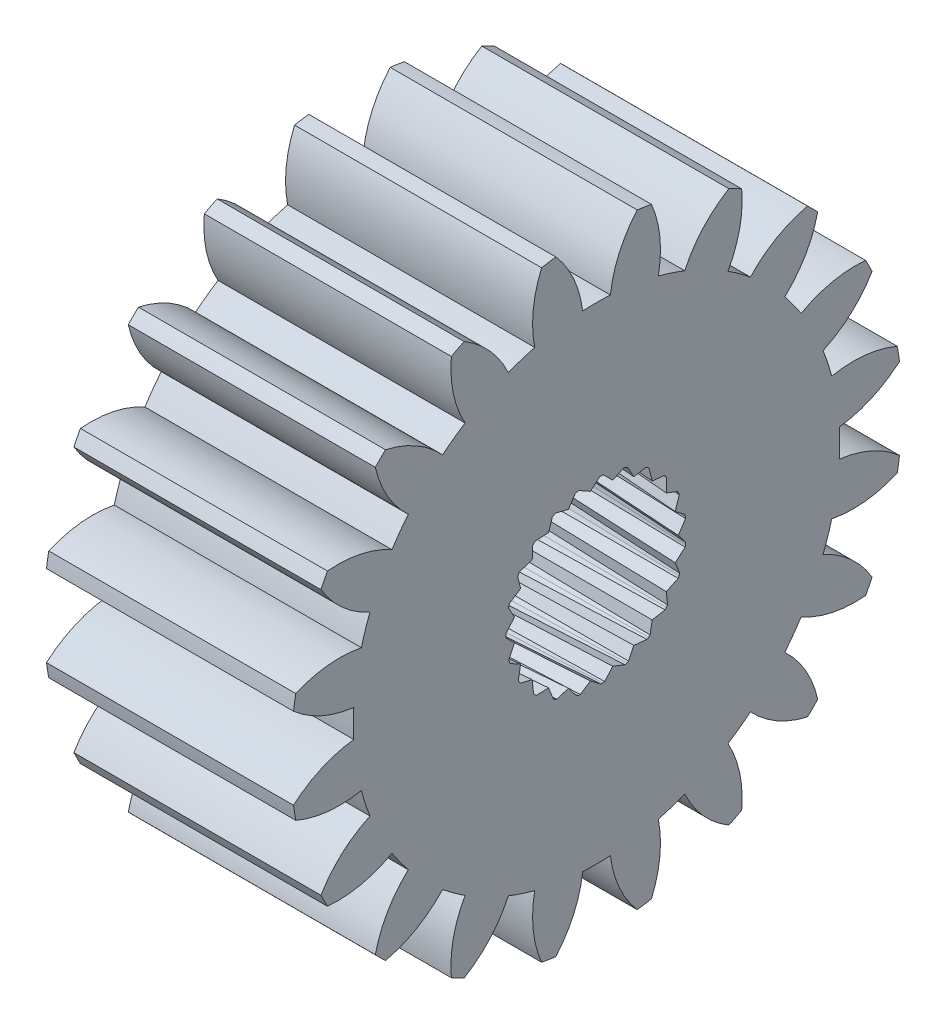
SolidWorks part; units mm, degrees
ref_plane "Plane1" through (0, 0, 0) normal (0, 0, 1) x (1, 0, 0)
ref_plane "Plane2" through (0, 0, 0) normal (0, 1, 0) x (1, 0, 0)
ref_plane "Plane3" through (0, 0, 0) normal (1, 0, 0) x (0, 0, -1)
sketch "HoldingSke" plane through (0, 0, 0) normal (0, 1, 0) x (1, 0, 0)
  line L0 (0, 0) -> (1.0441, -0.38)
  line L1 (-15, 0) -> (100, 0) construction
  line L2 (0, 0) -> (-2.1039, 2.3779)
  line L3 (0, 0) -> (-11.863, 4.5341)
  line L4 (0, 0) -> (8.1152, 2.9537)
  line L5 (0, 0) -> (-46.8476, -17.4728)
  line L6 (0, 0) -> (-6.6317, -4.4744)
  line L7 (-2.1039, 2.3779) -> (8.6586, 51.2059)
  line L8 (-76.2, 54.61) -> (-76.1, 54.61)
  line L9 (-71.009, 38.7566) -> (-53.1078, 45.2721)
  line L10 (-76.2, 71.12) -> (104.1128, 71.12)
  line L11 (0, 0) -> (-8, 0)
  line L12 (-76.2, 101.6) -> (-76.166, 101.6)
  line L13 (24.9733, 27.94) -> (52.9518, 28.4284)
  line L14 (24.9733, 27.94) -> (24.9743, 27.94)
  line L15 (24.9733, 27.94) -> (100.4006, 29.5858)
  line L16 (-63.627, -0.9) -> (-12.827, -0.9)
  circle A0 centre (0, 0) radius 0.4
  circle A1 centre (0, 0) radius 7.874
  circle A2 centre (0, 0) radius 37.5
  circle A3 centre (0, 0) radius 0.4
  dimension "MHD" = 15.748
  dimension "Hub_dia" = 75
  dimension "Bore" = 0.8
  dimension "MBD" = 0.8
  dimension "Num_teeth" = 20
  dimension "Pitch" = 1.1111
  dimension "Overall_len" = 50
  dimension "Show_teeth" = 20
  dimension "Thickness" = 8
  dimension "OAL" = 50.0001
  dimension "T_dim" = 0.1
  dimension "Ap" = 20
  dimension "H" = 19.05
  dimension "Pitch_radius" = 180.3128
  dimension "Width" = 8
  dimension "Backlash" = 0.034
  dimension "Addendum_fac" = 1
  dimension "Dedendum_fac" = 1.25
  dimension "Clearance_fac" = 0.25
  dimension "Dedendum_add" = 0.001
  dimension "Module" = 0.9
sketch "BasProSke" plane through (0, 0, 0) normal (0, 1, 0) x (1, 0, 0)
  line L0 (-10, 0) -> (60, 0) construction
  line L1 (0, 0) -> (0, 9.9)
  line L2 (0, 0) -> (8, 0)
  line L3 (8, 0) -> (8, 9.9)
  line L4 (8, 9.9) -> (0, 9.9)
  dimension "Thickness" = 8
  dimension "Diameter" = 19.8
revolve "Base-Revolve" add sketch "BasProSke" angle 360 about L0
sketch "TooCutSke" plane through (0, 0, 0) normal (1, 0, 0) x (0, 0, -1)
  line L1 (0, 0) -> (0, 107) construction
  line L2 (0, 0) -> (-0.7656, 8.9674) construction
  line L3 (0, 0) -> (-2.8085, 17.7324) construction
  line L4 (-0.7656, 8.9674) -> (-1.4043, 8.8662) construction
  arc A0 (0.4496, 7.8612) -> (-0.4496, 7.8612) centre (0, 0) ccw
  arc A1 (1.3383, 9.8348) -> (-1.3383, 9.8348) centre (0, 0) ccw
  circle A2 centre (0, 0) radius 9 construction
  circle A3 centre (0, 0) radius 8.4572 construction
  arc A4 (-0.4496, 7.8612) -> (-1.3383, 9.8348) centre (-4.0247, 7.4382) ccw
  arc A5 (1.3383, 9.8348) -> (0.4496, 7.8612) centre (4.0247, 7.4382) ccw
  dimension "Root_dia" = 15.748
  dimension "Overcut_dia" = 19.8508
  dimension "Pitch_dia" = 18
  dimension "Base_dia" = 16.9145
  dimension "Flank_rad" = 3.6
  dimension "Half_ang" = 9
  dimension "Half_CT" = 0.6466
extrude "ToothCut" cut sketch "TooCutSke" along normal through all
fillet "Breaks" [suppressed] radius 0.018
fillet "RootFillets" [suppressed] radius 0.226
pattern_circular "TeethCuts" count 20 every 18 about axis through (-10, 0, 0) along (1, 0, 0) of "ToothCut", "RootFillets", "Breaks"
sketch "HubNeaOneSke" plane through (0, 0, 0) normal (-1, 0, 0) x (0, 0, 1)
  circle A0 centre (0, 0) radius 7.874
  dimension "Diameter" = 15.748
extrude "HubNearOne" [suppressed] add sketch "HubNeaOneSke" along normal blind 42.0001
sketch "HubNeaBotSke" plane through (0, 0, 0) normal (-1, 0, 0) x (0, 0, 1)
  circle A0 centre (0, 0) radius 7.874
  dimension "Diameter" = 15.748
extrude "HubNearBoth" [suppressed] add sketch "HubNeaBotSke" along normal blind 21
ref_plane "FarPln" through (8, 0, 0) normal (1, 0, 0) x (0, 0, -1)
sketch "HubFarSke" plane through (8, 0, 0) normal (1, 0, 0) x (0, 0, -1)
  circle A0 centre (0, 0) radius 7.874
  dimension "Diameter" = 15.748
extrude "HubFar" [suppressed] add sketch "HubFarSke" along normal blind 21
sketch "BorSke" plane through (0, 0, 0) normal (1, 0, 0) x (0, 0, -1)
  circle A0 centre (0, 0) radius 0.4
  dimension "Diameter" = 0.8
extrude "Bore" cut sketch "BorSke" along normal mid plane 100.0001
sketch "KeySke" plane through (0, 0, 0) normal (1, 0, 0) x (0, 0, -1)
  line L0 (-0.05, 0) -> (-0.05, 0.5)
  line L1 (-0.05, 0.5) -> (0.05, 0.5)
  line L2 (0.05, 0.5) -> (0.05, 0)
  line L3 (0, 0) -> (0, 34) construction
  line L4 (-0.05, 0) -> (0.05, 0)
  dimension "Offset" = 0.5
  dimension "Width" = 0.1
extrude "Keyway" [suppressed] cut sketch "KeySke" along normal mid plane 100.0001
pattern_circular "Keyway2" [suppressed] count 2 every 90 about axis through (-10, 0, 0) along (1, 0, 0)
sketch "Sketch1" plane through (8, 0, 0) normal (1, 0, 0) x (0, 0, -1)
  line L185 (-2.934, 0.0633) -> (-2.6551, 0.3832)
  line L186 (-2.9384, 0) -> (-2.934, 0.0633)
  line L187 (-2.9384, 0) -> (-2.934, -0.0633)
  line L188 (-2.934, -0.0633) -> (-2.6551, -0.3422)
  line L189 (-2.8143, 0.8489) -> (-2.4594, 1.0817)
  line L190 (-2.8355, 0.7892) -> (-2.8143, 0.8489)
  line L191 (-2.8355, 0.7892) -> (-2.8484, 0.7271)
  line L192 (-2.8484, 0.7271) -> (-2.6551, 0.3832)
  line L193 (-2.487, 1.5731) -> (-2.0825, 1.7015)
  line L194 (-2.5236, 1.5213) -> (-2.487, 1.5731)
  line L195 (-2.5236, 1.5213) -> (-2.5528, 1.465)
  line L196 (-2.5528, 1.465) -> (-2.4594, 1.0817)
  line L197 (-1.9765, 2.1822) -> (-1.5523, 2.1967)
  line L198 (-2.0257, 2.1422) -> (-1.9765, 2.1822)
  line L199 (-2.0257, 2.1422) -> (-2.069, 2.0958)
  line L200 (-2.069, 2.0958) -> (-2.0825, 1.7015)
  line L201 (-1.3206, 2.6309) -> (-0.9082, 2.5304)
  line L202 (-1.3788, 2.6057) -> (-1.3206, 2.6309)
  line L203 (-1.3788, 2.6057) -> (-1.4329, 2.5727)
  line L204 (-1.4329, 2.5727) -> (-1.5523, 2.1967)
  line L205 (-0.5679, 2.8861) -> (-0.1979, 2.678)
  line L206 (-0.6308, 2.8774) -> (-0.5679, 2.8861)
  line L207 (-0.6308, 2.8774) -> (-0.6918, 2.8603)
  line L208 (-0.6918, 2.8603) -> (-0.9082, 2.5304)
  line L209 (0.2257, 2.9287) -> (0.5258, 2.6285)
  line L210 (0.1628, 2.9373) -> (0.2257, 2.9287)
  line L211 (0.1628, 2.9373) -> (0.0994, 2.9373)
  line L212 (0.0994, 2.9373) -> (-0.1979, 2.678)
  line L213 (1.0013, 2.7556) -> (1.2093, 2.3856)
  line L214 (0.9431, 2.7808) -> (1.0013, 2.7556)
  line L215 (0.9431, 2.7808) -> (0.8821, 2.7979)
  line L216 (0.8821, 2.7979) -> (0.5258, 2.6285)
  line L217 (1.7015, 2.3796) -> (1.802, 1.9672)
  line L218 (1.6523, 2.4197) -> (1.7015, 2.3796)
  line L219 (1.6523, 2.4197) -> (1.5981, 2.4526)
  line L220 (1.5981, 2.4526) -> (1.2093, 2.3856)
  line L221 (2.2743, 1.8287) -> (2.2598, 1.4045)
  line L222 (2.2377, 1.8806) -> (2.2743, 1.8287)
  line L223 (2.2377, 1.8806) -> (2.1944, 1.9269)
  line L224 (2.1944, 1.9269) -> (1.802, 1.9672)
  line L225 (2.6772, 1.1437) -> (2.5488, 0.7392)
  line L226 (2.656, 1.2035) -> (2.6772, 1.1437)
  line L227 (2.656, 1.2035) -> (2.6268, 1.2598)
  line L228 (2.6268, 1.2598) -> (2.2598, 1.4045)
  line L229 (2.8804, 0.3754) -> (2.6476, 0.0205)
  line L230 (2.8761, 0.4387) -> (2.8804, 0.3754)
  line L231 (2.8761, 0.4387) -> (2.8632, 0.5008)
  line L232 (2.8632, 0.5008) -> (2.5488, 0.7392)
  line L233 (2.8687, -0.4192) -> (2.5488, -0.6982)
  line L234 (2.8816, -0.3571) -> (2.8687, -0.4192)
  line L235 (2.8816, -0.3571) -> (2.886, -0.2939)
  line L236 (2.886, -0.2939) -> (2.6476, 0.0205)
  line L237 (2.6431, -1.1813) -> (2.2598, -1.3636)
  line L238 (2.6723, -1.1249) -> (2.6431, -1.1813)
  line L239 (2.6723, -1.1249) -> (2.6935, -1.0652)
  line L240 (2.6935, -1.0652) -> (2.5488, -0.6982)
  line L241 (2.2203, -1.8542) -> (1.802, -1.9263)
  line L242 (2.2636, -1.8078) -> (2.2203, -1.8542)
  line L243 (2.2636, -1.8078) -> (2.3001, -1.756)
  line L244 (2.3001, -1.756) -> (2.2598, -1.3636)
  line L245 (1.6316, -2.388) -> (1.2093, -2.3446)
  line L246 (1.6858, -2.3551) -> (1.6316, -2.388)
  line L247 (1.6858, -2.3551) -> (1.735, -2.315)
  line L248 (1.735, -2.315) -> (1.802, -1.9263)
  line L249 (0.9207, -2.7433) -> (0.5258, -2.5876)
  line L250 (0.9817, -2.7262) -> (0.9207, -2.7433)
  line L251 (0.9817, -2.7262) -> (1.0399, -2.7009)
  line L252 (1.0399, -2.7009) -> (1.2093, -2.3446)
  line L253 (0.1403, -2.8935) -> (-0.1979, -2.6371)
  line L254 (0.2037, -2.8935) -> (0.1403, -2.8935)
  line L255 (0.2037, -2.8935) -> (0.2665, -2.8849)
  line L256 (0.2665, -2.8849) -> (0.5258, -2.5876)
  line L257 (-0.6517, -2.8277) -> (-0.9082, -2.4895)
  line L258 (-0.5906, -2.8448) -> (-0.6517, -2.8277)
  line L259 (-0.5906, -2.8448) -> (-0.5278, -2.8534)
  line L260 (-0.5278, -2.8534) -> (-0.1979, -2.6371)
  line L261 (-1.3966, -2.5506) -> (-1.5523, -2.1557)
  line L262 (-1.3424, -2.5835) -> (-1.3966, -2.5506)
  line L263 (-1.3424, -2.5835) -> (-1.2842, -2.6088)
  line L264 (-1.2842, -2.6088) -> (-0.9082, -2.4895)
  line L265 (-2.039, -2.0828) -> (-2.0825, -1.6606)
  line L266 (-1.9958, -2.1292) -> (-2.039, -2.0828)
  line L267 (-1.9958, -2.1292) -> (-1.9466, -2.1692)
  line L268 (-1.9466, -2.1692) -> (-1.5523, -2.1557)
  line L269 (-2.5315, -1.459) -> (-2.4594, -1.0408)
  line L270 (-2.5023, -1.5154) -> (-2.5315, -1.459)
  line L271 (-2.5023, -1.5154) -> (-2.4657, -1.5672)
  line L272 (-2.4657, -1.5672) -> (-2.0825, -1.6606)
  line L273 (-2.8374, -0.7256) -> (-2.6551, -0.3422)
  line L274 (-2.8245, -0.7876) -> (-2.8374, -0.7256)
  line L275 (-2.8245, -0.7876) -> (-2.8032, -0.8474)
  line L276 (-2.8032, -0.8474) -> (-2.4594, -1.0408)
  point P0 (0, 0)
  point P21 (0, 0)
  point P93 (-2.9362, -0.0316)
  point P123 (-0.0162, 0.0205)
  dimension "D1" = 2.6551
  dimension "D2" = 2.934
  dimension "D3" = 2.9362
  dimension "D4" = 0.0633
  dimension "D5" = 0.3627
  dimension "D6" = 23
  dimension "D8" = 0.3422
extrude "Cut-Extrude1" cut sketch "Sketch1" against normal blind 10 draft 3
sketch "Sketch2" plane through (8, 0, 0) normal (1, 0, 0) x (0, 0, -1)
  circle A0 centre (0, 0) radius 7.874
  arc A1 (-7.3375, 2.8568) -> (-7.6153, 2.0016) centre (0, 0) ccw construction
  dimension "D1" = 15.748
equation "' \"Module@HoldingSke\" = 6.35"
equation "' \"Num_teeth@HoldingSke\" = 12"
equation "' \"Ap@HoldingSke\" =  20"
equation "' \"Ap@HoldingSke\" = 20"
equation "' \"Width@HoldingSke\" = 0.5 * 25.4"
equation "' \"Hub_dia@HoldingSke\"= 1 * 25.4"
equation "' \"Hub_dia@HoldingSke\" = 1 * 25.4"
equation "' \"Overall_len@HoldingSke\" = 1.0 * 25.4"
equation "' \"Bore@HoldingSke\" = 0.75 * 25.4"
equation "' \"T_dim@HoldingSke\" = 0.1 * 25.4"
equation "' \"Width@KeySke\" = 0.25 * 25.4"
equation "' \"Show_teeth@HoldingSke\" = 13"
equation "' \"Backlash@HoldingSke\" = 0.009 * 25.4"
equation "' \"Addendum_fac@HoldingSke\" = 1.0"
equation "' \"Dedendum_fac@HoldingSke\" = 1.25"
equation "' \"Dedendum_add@HoldingSke\" = 0.00005 * 25.4"
equation "' \"Clearance_fac@HoldingSke\" = 0.25"
equation "\"Pitch@HoldingSke\" = 1 / \"Module@HoldingSke\""
equation "\"Overcut_dia@TooCutSke\" = (\"Num_teeth@HoldingSke\" + 2 * \"Addendum_fac@HoldingSke\") / \"Pitch@HoldingSke\" + 0.002 * 25.4"
equation "\"Pitch_dia@TooCutSke\" = \"Num_teeth@HoldingSke\" / \"Pitch@HoldingSke\""
equation "\"Base_dia@TooCutSke\" = \"Num_teeth@HoldingSke\" / \"Pitch@HoldingSke\" * cos((\"Ap@HoldingSke\"  * 3.14159265 / 180))"
equation "\"Root_dia@TooCutSke\" = (\"Num_teeth@HoldingSke\" + 2) / \"Pitch@HoldingSke\" - 2 * (\"Addendum_fac@HoldingSke\" + \"Dedendum_fac@HoldingSke\") / \"Pitch@HoldingSke\" - \"Dedendum_add@HoldingSke\" * 2"
equation "\"Half_ang@TooCutSke\" = 180 / \"Num_teeth@HoldingSke\""
equation "\"Half_CT@TooCutSke\" = \"Num_teeth@HoldingSke\" / \"Pitch@HoldingSke\" * sin((3.14159265 / 2 / \"Num_teeth@HoldingSke\")) / 2 - 7 * \"Backlash@HoldingSke\" / 4"
equation "\"Flank_rad@TooCutSke\" = \"Num_teeth@HoldingSke\" / \"Pitch@HoldingSke\" / 5"
equation "\"Radius@RootFillets\" = \"Clearance_fac@HoldingSke\" / \"Pitch@HoldingSke\" + \"Dedendum_add@HoldingSke\""
equation "\"Break_rad@Breaks\" = 0.02 / \"Pitch@HoldingSke\""
equation "\"Thickness@HoldingSke\" = \"Width@HoldingSke\""
equation "\"OAL@HoldingSke\" = \"Thickness@HoldingSke\""
equation "\"MHD@HoldingSke\" = (\"Num_teeth@HoldingSke\" + 2) / \"Pitch@HoldingSke\" - 2 * (\"Addendum_fac@HoldingSke\" + \"Dedendum_fac@HoldingSke\")  / \"Pitch@HoldingSke\" - \"Dedendum_add@HoldingSke\" * 2"
equation "\"MBD@HoldingSke\" = (\"Num_teeth@HoldingSke\" + 2) / \"Pitch@HoldingSke\" - 2 * (\"Addendum_fac@HoldingSke\" + \"Dedendum_fac@HoldingSke\")  / \"Pitch@HoldingSke\" - \"Dedendum_add@HoldingSke\" * 2 - 0.002 * 25.4"
equation "\"MHD@HoldingSke\" = ((sgn( \"MHD@HoldingSke\" - \"Hub_dia@HoldingSke\" )-1)*( \"MHD@HoldingSke\" - \"Hub_dia@HoldingSke\" ))/-2+ \"Hub_dia@HoldingSke\""
equation "\"MBD@HoldingSke\" = ((sgn( \"MBD@HoldingSke\" - \"Bore@HoldingSke\" )-1)*( \"MBD@HoldingSke\" - \"Bore@HoldingSke\" ))/-2+ \"Bore@HoldingSke\""
equation "\"OAL@HoldingSke\" = ((sgn( \"OAL@HoldingSke\" - \"Overall_len@HoldingSke\" )+1)*( \"OAL@HoldingSke\" - \"Overall_len@HoldingSke\" ))/2 + \"Overall_len@HoldingSke\" + 0.000002 * 25.4"
equation "\"Num_teeth@TeethCuts\" = int( \"Show_teeth@HoldingSke\" ) + 1"
equation "\"Num_teeth@TeethCuts\" = ((sgn( \"Num_teeth@TeethCuts\" - \"Num_teeth@HoldingSke\" )-1)*( \"Num_teeth@TeethCuts\" - \"Num_teeth@HoldingSke\" ))/-2+ \"Num_teeth@HoldingSke\""
equation "\"Num_teeth@TeethCuts\" = ((sgn( \"Num_teeth@TeethCuts\" - 2.0)+1)*( \"Num_teeth@TeethCuts\" - 2.0))/2 +2.0"
equation "\"Angle@TeethCuts\" = 360.0 / \"Num_teeth@HoldingSke\""
equation "\"Diameter@BasProSke\" = (\"Num_teeth@HoldingSke\" + 2 * \"Addendum_fac@HoldingSke\") / \"Pitch@HoldingSke\""
equation "\"Thickness@BasProSke\"  = \"Thickness@HoldingSke\""
equation "' \"Fillet_rad@BasProSke\" =  \"Thickness@HoldingSke\" * 0.05"
equation "' \"Fillet_rad@BasProSke\" = \"Thickness@HoldingSke\" * 0.05"
equation "\"MHD@HoldingSke\" = ((sgn( \"MHD@HoldingSke\" - \"Root_dia@TooCutSke\" )-1)*( \"MHD@HoldingSke\" - \"Root_dia@TooCutSke\" ))/-2+ \"Root_dia@TooCutSke\""
equation "\"Diameter@HubNeaOneSke\" = \"MHD@HoldingSke\""
equation "\"Length@HubNearOne\" = \"OAL@HoldingSke\" - \"Thickness@BasProSke\""
equation "\"Diameter@HubNeaBotSke\" = \"MHD@HoldingSke\""
equation "\"Length@HubNearBoth\" = ( \"OAL@HoldingSke\" - \"Thickness@BasProSke\" ) / 2.0"
equation "\"Thickness@FarPln\" = \"Thickness@BasProSke\""
equation "\"Diameter@HubFarSke\" = \"MHD@HoldingSke\""
equation "\"Length@HubFar\" = ( \"OAL@HoldingSke\" - \"Thickness@BasProSke\" ) / 2.0"
equation "\"Diameter@BorSke\" = \"MBD@HoldingSke\""
equation "\"D1@Bore\" = \"OAL@HoldingSke\" * 2.0"
equation "\"D1@Keyway\" = \"OAL@HoldingSke\" * 2.0"
equation "\"Offset@KeySke\" = \"T_dim@HoldingSke\" + \"MBD@HoldingSke\" / 2.0"
